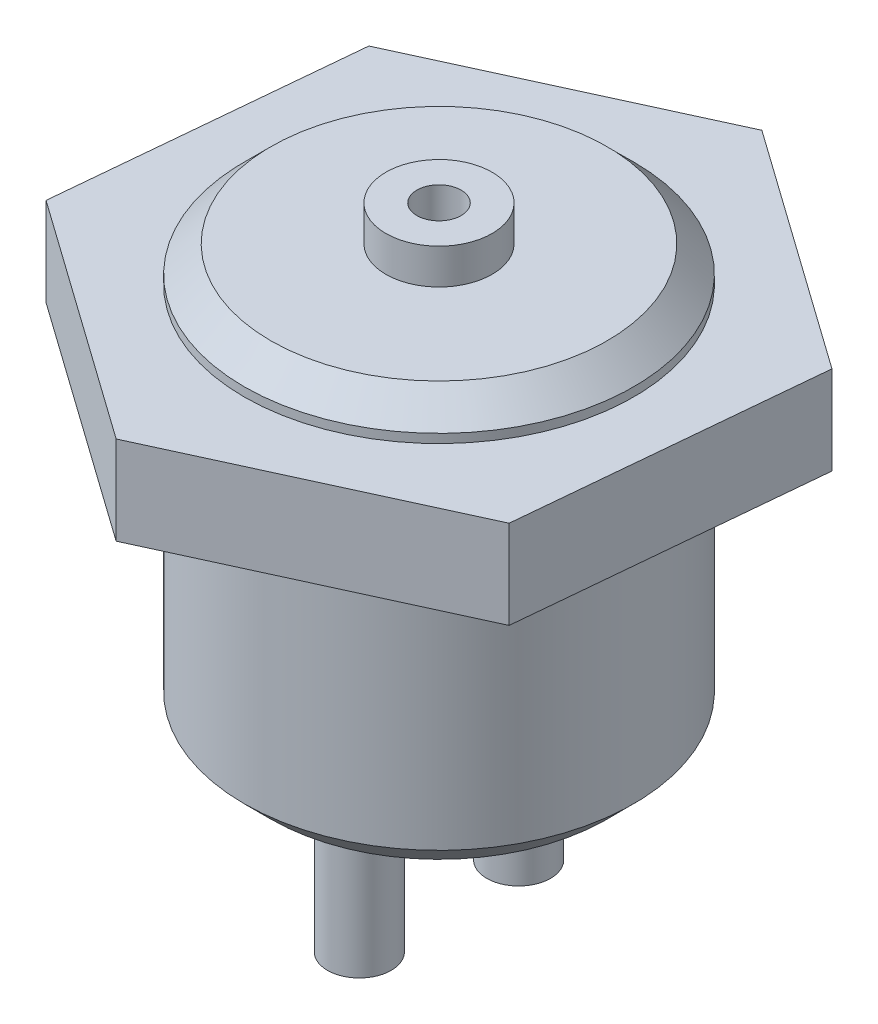
SolidWorks part; units mm, degrees
material "SKD11淬火HRC56-60"
ref_plane "前基準面" through (0, 0, 0) normal (0, 0, 1) x (1, 0, 0)
ref_plane "上基準面" through (0, 0, 0) normal (0, 1, 0) x (1, 0, 0)
ref_plane "右基準面" through (0, 0, 0) normal (1, 0, 0) x (0, 0, -1)
sketch "草图1" plane through (0, 0, 0) normal (0, 1, 0) x (1, 0, 0)
  circle A0 centre (0, 0) radius 11
  dimension "D1" = 22
extrude "凸台-拉伸1" add sketch "草图1" along normal blind 23.4
sketch "草图2" plane through (0, 23.4, 0) normal (0, 1, 0) x (1, 0, 0)
  circle A0 centre (0, 0) radius 3
  dimension "D1" = 6
extrude "凸台-拉伸2" add sketch "草图2" along normal blind 2
hole_wizard "M3 螺纹孔1" positions "草图4" profile "草图3" tap size "M3" standard "ISO"
sketch "草图4" plane through (0, 25.4, 0) normal (0, 1, 0) x (-1, 0, 0)
  point P0 (0, 0)
sketch "草图3" plane through (0, 25.4, 0) normal (1, 0, 0) x (0, 0, 1)
  line L0 (0, 0) -> (0, 8.2511)
  line L1 (0, 8.2511) -> (1.25, 7.5)
  line L2 (1.25, 7.5) -> (1.25, 0)
  line L5 (1.25, 0) -> (0, 0)
  line L10 (0, 8.2511) -> (-1.25, 7.5) construction
  line L11 (0, -6.35) -> (0, 107.95) construction
  dimension "螺纹孔钻头直径" = 2.5
  dimension "螺纹孔钻头深度" = 7.5
  dimension "导头角度" = 118
cosmetic thread "孔螺蚊线1" parameters "D1"=6, "D2"=3
chamfer "倒角1" distance 1.5 angle 45 1 edges at (0, 23.4, 11)
chamfer "倒角2" distance 1.5 angle 45 1 edges at (0, 0, 11)
sketch "草图5" plane through (0, 0, 0) normal (0, -1, 0) x (1, 0, 0)
  line L0 (0, 0) -> (0, 7.0758) construction
  line L1 (0, 0) -> (4.629, 0) construction
  circle A0 centre (0, 4.5) radius 1.8
  circle A1 centre (0, -4.5) radius 1.8
  dimension "D1" = 3.6
  dimension "D2" = 9
extrude "凸台-拉伸3" add sketch "草图5" along normal blind 9
ref_plane "基准面1" through (0, 16.4, 0) normal (0, 1, 0) x (-1, 0, 0)
sketch "草图6" plane through (0, 16.4, 0) normal (0, 1, 0) x (-1, 0, 0)
  line L1 (13.6527, -9.6921) -> (15.22, 6.9776)
  line L2 (15.22, 6.9776) -> (1.5672, 16.6696)
  line L3 (1.5672, 16.6696) -> (-13.6527, 9.6921)
  line L4 (-13.6527, 9.6921) -> (-15.22, -6.9776)
  line L5 (-15.22, -6.9776) -> (-1.5672, -16.6696)
  line L6 (-1.5672, -16.6696) -> (13.6527, -9.6921)
  circle A0 centre (0, 0) radius 14.5 construction
  dimension "D1" = 29
extrude "凸台-拉伸4" add sketch "草图6" along normal blind 5
